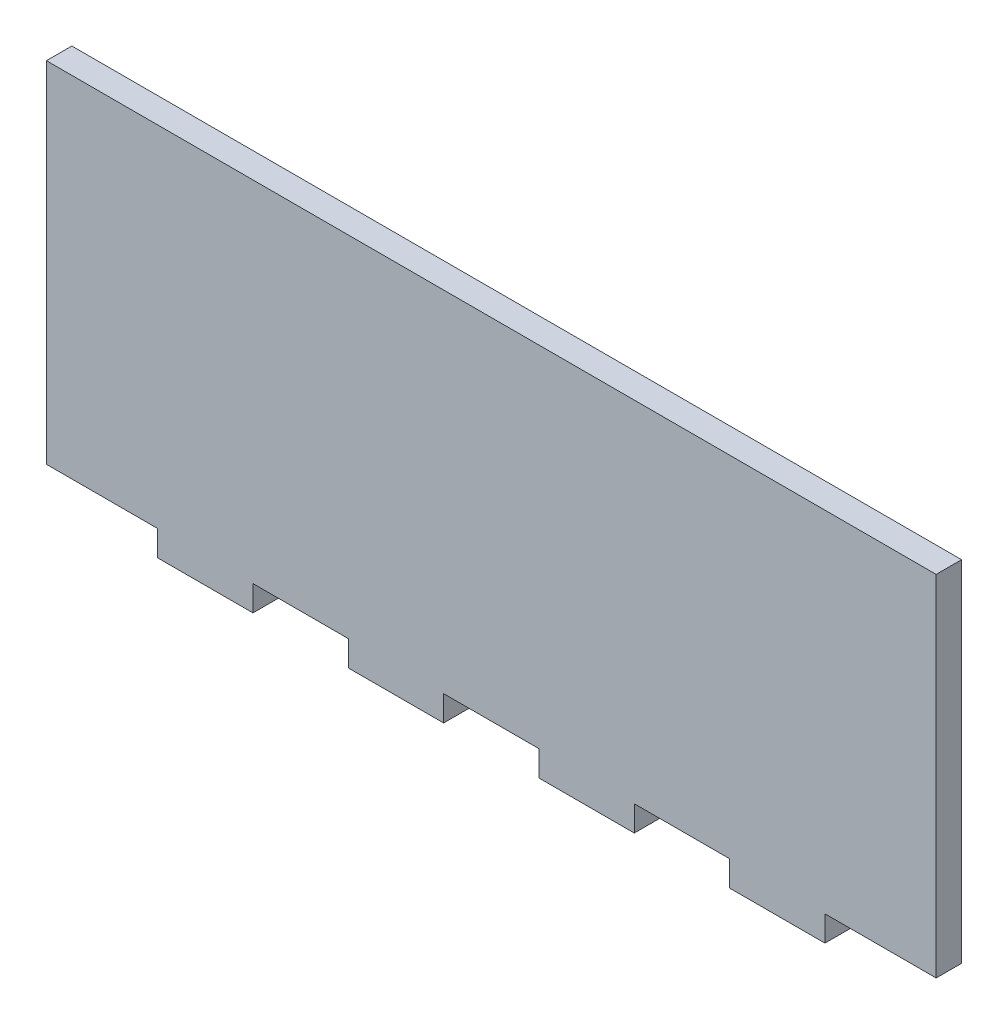
SolidWorks part; units mm, degrees
ref_plane "Front Plane" through (0, 0, 0) normal (0, 0, 1) x (1, 0, 0)
ref_plane "Top Plane" through (0, 0, 0) normal (0, 1, 0) x (1, 0, 0)
ref_plane "Right Plane" through (0, 0, 0) normal (1, 0, 0) x (0, 0, -1)
sketch "Sketch1" plane through (0, 0, 0) normal (0, 1, 0) x (1, 0, 0)
  line L1 (-70, -2) -> (70, -2)
  line L2 (-70, -2) -> (-70, 2)
  line L3 (-70, 2) -> (70, 2)
  line L4 (70, -2) -> (70, 2)
  line L5 (-70, -2) -> (70, 2) construction
  line L6 (-70, 2) -> (70, -2) construction
  point P0 (0, 0)
  dimension "D1" = 4
  dimension "D2" = 140
extrude "Boss-Extrude1" add sketch "Sketch1" along normal blind 55
sketch "Sketch2" plane through (0, 0, 0) normal (0, -1, 0) x (-1, 0, 0)
  line L0 (-70, 2) -> (70, 2) construction
  line L1 (52.5, 2) -> (37.5, 2)
  line L2 (52.5, 2) -> (52.5, -2)
  line L3 (52.5, -2) -> (37.5, -2)
  line L4 (37.5, 2) -> (37.5, -2)
  line L5 (70, -2) -> (-70, -2) construction
  line L6 (0, 2.2) -> (0, -2.2) construction
  line L7 (22.5, 2) -> (7.5, 2)
  line L8 (22.5, 2) -> (22.5, -2)
  line L9 (22.5, -2) -> (7.5, -2)
  line L10 (7.5, 2) -> (7.5, -2)
  line L11 (-7.5, 2) -> (-22.5, 2)
  line L12 (-7.5, 2) -> (-7.5, -2)
  line L13 (-7.5, -2) -> (-22.5, -2)
  line L14 (-22.5, 2) -> (-22.5, -2)
  line L15 (-37.5, 2) -> (-52.5, 2)
  line L16 (-37.5, 2) -> (-37.5, -2)
  line L17 (-37.5, -2) -> (-52.5, -2)
  line L18 (-52.5, 2) -> (-52.5, -2)
  dimension "D1" = 15
  dimension "D2" = 15
  dimension "D3" = 15
  dimension "D4" = 15
  dimension "D5" = 15
  dimension "D6" = 15
  dimension "D7" = 15
  dimension "D8" = 7.5
extrude "Boss-Extrude2" add sketch "Sketch2" along normal blind 4
